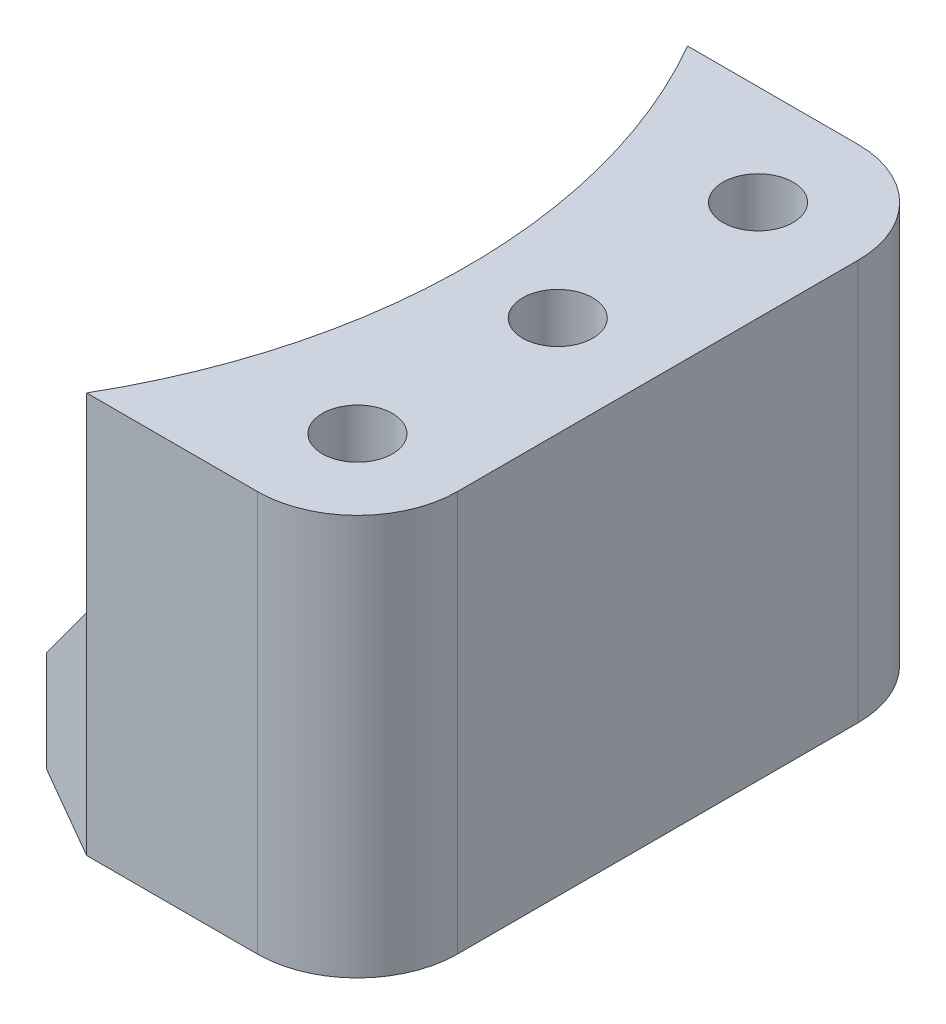
SolidWorks part; units mm, degrees
material "ABS PC"
ref_plane "Front Plane" through (0, 0, 0) normal (0, 0, 1) x (1, 0, 0)
ref_plane "Top Plane" through (0, 0, 0) normal (0, 1, 0) x (1, 0, 0)
ref_plane "Right Plane" through (0, 0, 0) normal (1, 0, 0) x (0, 0, -1)
sketch "Sketch1" plane through (0, 0, 0) normal (0, 0, 1) x (1, 0, 0)
  line L0 (30, 20) -> (30, 10.5)
  line L1 (30, 10.5) -> (24.5, 5)
  line L2 (24.5, 5) -> (24.5, 0)
  line L3 (10.0553, 0) -> (-10.0553, 0) construction
  line L4 (24.5, 0) -> (44.5, 0)
  line L5 (44.5, 0) -> (44.5, 20)
  line L6 (44.5, 20) -> (30, 20)
  line L7 (0, 0) -> (0, 60.3942) construction
  line L8 (0, -11) -> (0, 11) construction
  dimension "D1" = 30
  dimension "D2" = 5
  dimension "D3" = 20
  dimension "D4" = 45
  dimension "D5" = 20
  dimension "D6" = 10.5
revolve "Revolve1" add sketch "Sketch1" angle 60 mid plane about L7
sketch "Sketch2" plane through (0, 0, 0) normal (0, 1, 0) x (1, 0, 0)
  line L0 (-11, 0) -> (11, 0) construction
  line L1 (39.5, -15) -> (11.8624, -15)
  line L2 (39.5, -15) -> (39.5, 15)
  line L3 (39.5, 15) -> (11.8624, 15)
  line L4 (11.8624, -15) -> (11.8624, 15)
  line L5 (0, -11) -> (0, 11) construction
  dimension "D1" = 15
  dimension "D2" = 30
  dimension "D3" = 39.5
extrude "Cut-Extrude2" cut sketch "Sketch2" along normal blind 40 flip side to cut
fillet "Fillet1" radius 5 2 edges at (39.5, 10, -15) (39.5, 10, 15)
sketch "Sketch3" plane through (0, 20, 0) normal (0, 1, 0) x (1, 0, 0)
  line L2 (39.5, 10) -> (39.5, -10) construction
  line L3 (-10.0553, 0) -> (10.0553, 0) construction
  circle A0 centre (34.5, -10) radius 1.75
  circle A1 centre (34.5, 10) radius 1.75
  circle A2 centre (34.5, 0) radius 1.75
  dimension "D1" = 3.5
  dimension "D2" = 5
  dimension "D3" = 10
  dimension "D4" = 10
extrude "Cut-Extrude3" cut sketch "Sketch3" against normal blind 40
